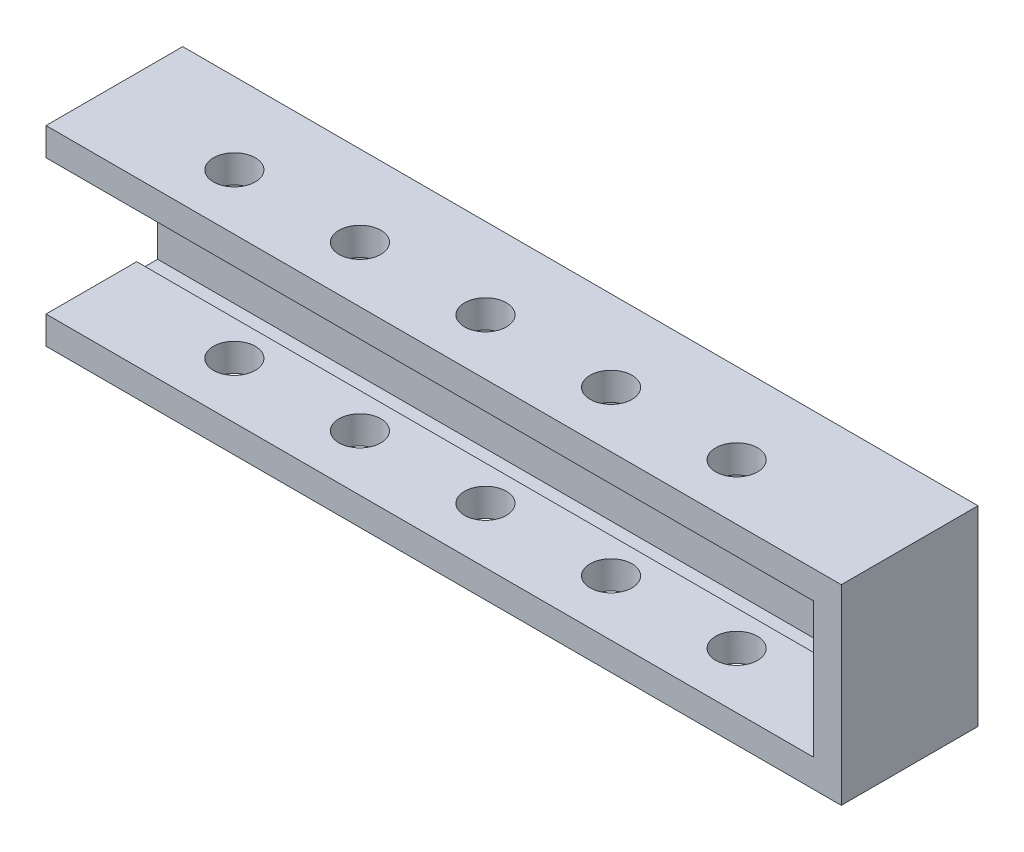
SolidWorks part; units mm, degrees
ref_plane "Спереди" through (0, 0, 0) normal (0, 0, 1) x (1, 0, 0)
ref_plane "Сверху" through (0, 0, 0) normal (0, 1, 0) x (1, 0, 0)
ref_plane "Справа" through (0, 0, 0) normal (1, 0, 0) x (0, 0, -1)
sketch "Эскиз1" plane through (0, 0, 0) normal (0, 0, 1) x (1, 0, 0)
  line L1 (0, 0) -> (57, 0)
  line L2 (0, 0) -> (0, 13.7)
  line L3 (0, 13.7) -> (57, 13.7)
  line L4 (57, 0) -> (57, 13.7)
  dimension "D1" = 13.7
  dimension "D2" = 57
extrude "Бобышка-Вытянуть1" add sketch "Эскиз1" along normal blind 9.8
sketch "Эскиз2" plane through (0, 0, 9.8) normal (0, 0, 1) x (1, 0, 0)
  line L0 (0, 13.7) -> (0, 0) construction
  line L1 (0, 11.7) -> (55, 11.7)
  line L2 (0, 11.7) -> (0, 2)
  line L3 (0, 2) -> (55, 2)
  line L4 (55, 11.7) -> (55, 2)
  line L5 (57, 0) -> (57, 13.7) construction
  dimension "D1" = 2
  dimension "D2" = 2
  dimension "D3" = 2
extrude "Вырез-Вытянуть1" cut sketch "Эскиз2" against normal blind 8
sketch "Эскиз3" plane through (0, 0, 1.8) normal (0, 0, 1) x (1, 0, 0)
  line L1 (0, 11.7) -> (54.9721, 11.7)
  line L2 (0, 11.7) -> (0, 12.3)
  line L3 (0, 12.3) -> (54.9721, 12.3)
  line L4 (54.9721, 11.7) -> (54.9721, 12.3)
  line L5 (0, 2) -> (54.9721, 2)
  line L6 (0, 2) -> (0, 1.4)
  line L7 (0, 1.4) -> (54.9721, 1.4)
  line L8 (54.9721, 2) -> (54.9721, 1.4)
  dimension "D1" = 0.6
  dimension "D2" = 0.6
extrude "Вырез-Вытянуть2" cut sketch "Эскиз3" along normal blind 1.5
sketch "Эскиз4" plane through (0, 13.7, 0) normal (0, 1, 0) x (1, 0, 0)
  line L2 (57, -9.8) -> (0, -9.8) construction
  circle A0 centre (45.5, -5.8) radius 1.5
  circle A1 centre (36.5, -5.8) radius 1.5
  circle A2 centre (27.5, -5.8) radius 1.5
  circle A3 centre (18.5, -5.8) radius 1.5
  circle A4 centre (9.5, -5.8) radius 1.5
  dimension "D1" = 3
  dimension "D2" = 45.5
  dimension "D4" = 3
  dimension "D5" = 3
  dimension "D6" = 3
  dimension "D10" = 3
  dimension "D3" = 4
  dimension "D7" = 9
  dimension "D8" = 9
  dimension "D9" = 9
  dimension "D11" = 9
extrude "Вырез-Вытянуть3" cut sketch "Эскиз4" against normal blind 14
